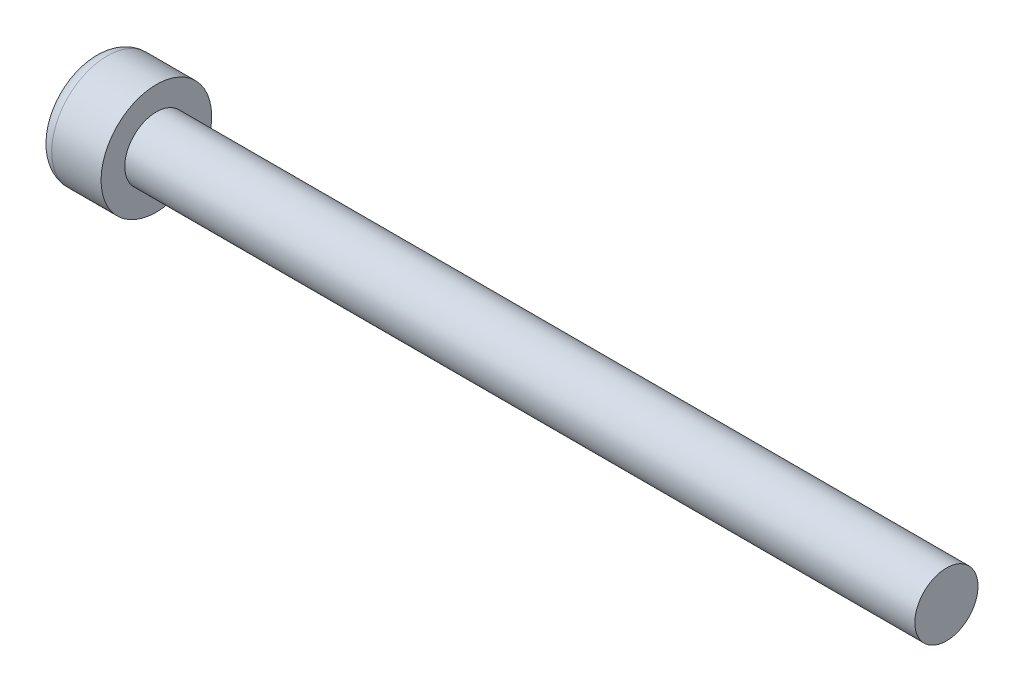
SolidWorks part; units mm, degrees
material "Plain Carbon Steel"
ref_plane "Front Plane" through (0, 0, 0) normal (0, 0, 1) x (1, 0, 0)
ref_plane "Top Plane" through (0, 0, 0) normal (0, 1, 0) x (1, 0, 0)
ref_plane "Right Plane" through (0, 0, 0) normal (1, 0, 0) x (0, 0, -1)
sketch "Sketch1" plane through (0, 0, 0) normal (0, 0, 1) x (1, 0, 0)
  line L0 (0, 0) -> (0, 2.625)
  line L1 (0.875, 3.5) -> (4, 3.5)
  line L2 (4, 3.5) -> (4, 2)
  line L3 (4, 2) -> (54, 2)
  line L4 (54, 2) -> (54, 0)
  line L5 (54, 0) -> (0, 0) construction
  line L6 (0.875, 2.625) -> (0.875, 1.75) construction
  line L7 (0.875, 1.75) -> (0.875, 0.875) construction
  line L8 (0.875, 0.875) -> (0.875, 0) construction
  line L9 (0.875, 3.5) -> (0.875, 2.625) construction
  line L10 (0, 0) -> (54, 0)
  arc A0 (0, 2.625) -> (0.875, 3.5) centre (0.875, 2.625) cw
  dimension "D1" = 4
  dimension "D2" = 7
  dimension "D3" = 4
  dimension "D4" = 50
revolve "Revolve1" add sketch "Sketch1" angle 360 about L10
sketch "Sketch2" plane through (0, 0, 0) normal (-1, 0, 0) x (0, 0, 1)
  line L1 (0, 1.7321) -> (-1.5, 0.866)
  line L2 (-1.5, 0.866) -> (-1.5, -0.866)
  line L3 (-1.5, -0.866) -> (0, -1.7321)
  line L4 (0, -1.7321) -> (1.5, -0.866)
  line L5 (1.5, -0.866) -> (1.5, 0.866)
  line L6 (1.5, 0.866) -> (0, 1.7321)
  circle A0 centre (0, 0) radius 1.5 construction
  dimension "D1" = 3
extrude "Cut-Extrude1" cut sketch "Sketch2" against normal blind 2
